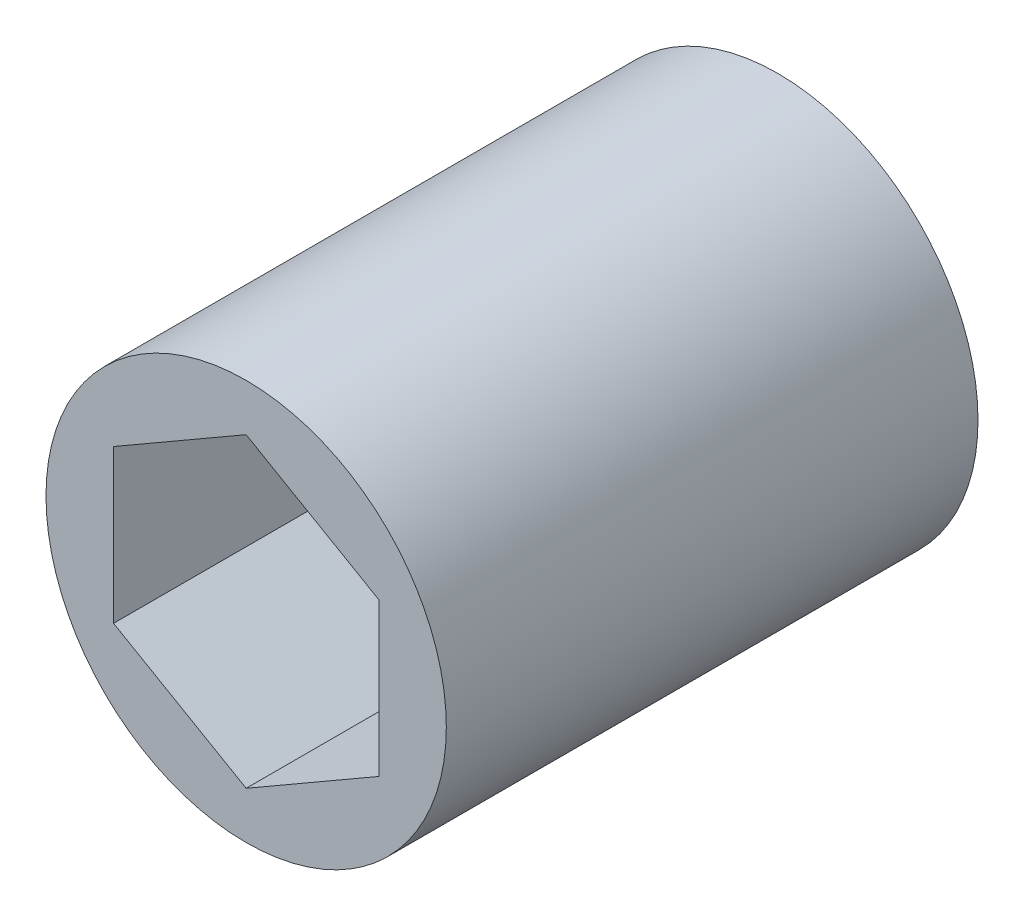
SolidWorks part; units mm, degrees
material "PET"
ref_plane "Front Plane" through (0, 0, 0) normal (0, 0, 1) x (1, 0, 0)
ref_plane "Top Plane" through (0, 0, 0) normal (0, 1, 0) x (1, 0, 0)
ref_plane "Right Plane" through (0, 0, 0) normal (1, 0, 0) x (0, 0, -1)
sketch "Sketch1" plane through (0, 0, 0) normal (0, 0, 1) x (1, 0, 0)
  line L1 (6.731, 3.8861) -> (0, 7.7723)
  line L2 (0, 7.7723) -> (-6.731, 3.8861)
  line L3 (-6.731, 3.8861) -> (-6.731, -3.8861)
  line L4 (-6.731, -3.8861) -> (0, -7.7723)
  line L5 (0, -7.7723) -> (6.731, -3.8861)
  line L6 (6.731, -3.8861) -> (6.731, 3.8861)
  circle A0 centre (0, 0) radius 6.731 construction
  circle A1 centre (0, 0) radius 10.16
  dimension "D1" = 13.462
  dimension "D2" = 20.32
extrude "Boss-Extrude1" add sketch "Sketch1" along normal blind 26.9875
